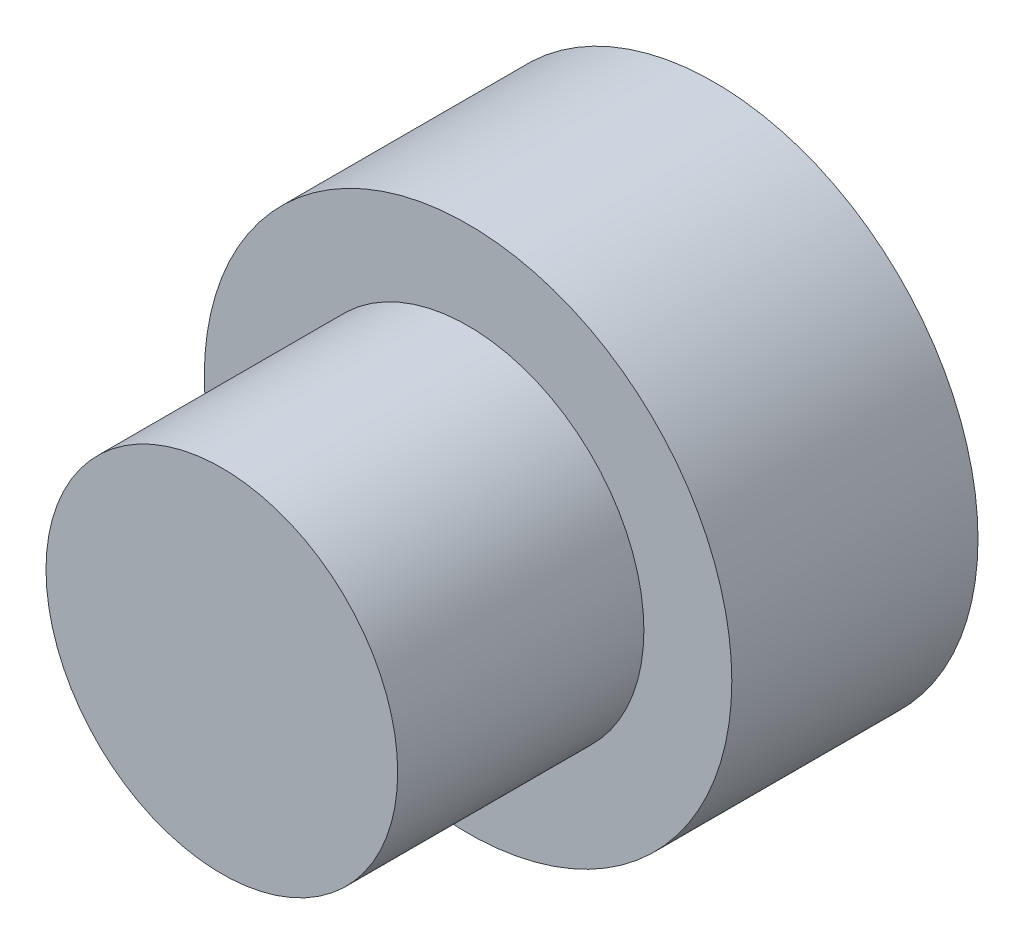
SolidWorks part; units mm, degrees
ref_plane "Front Plane" through (0, 0, 0) normal (0, 0, 1) x (1, 0, 0)
ref_plane "Top Plane" through (0, 0, 0) normal (0, 1, 0) x (1, 0, 0)
ref_plane "Right Plane" through (0, 0, 0) normal (1, 0, 0) x (0, 0, -1)
sketch "Sketch1" plane through (0, 0, 0) normal (0, 0, 1) x (1, 0, 0)
  circle A0 centre (0, 0) radius 7.5
extrude "Boss-Extrude1" add sketch "Sketch1" along normal blind 7 contours A0
sketch "Sketch2" plane through (0, 0, 7) normal (0, 0, 1) x (1, 0, 0)
  circle A0 centre (0, 0) radius 5
extrude "Boss-Extrude2" add sketch "Sketch2" along normal blind 7
sketch "Sketch3" plane through (0, 0, 0) normal (0, 0, -1) x (-1, 0, 0)
  circle A0 centre (0, 0) radius 2.5
extrude "Cut-Extrude1" cut sketch "Sketch3" against normal blind 6
